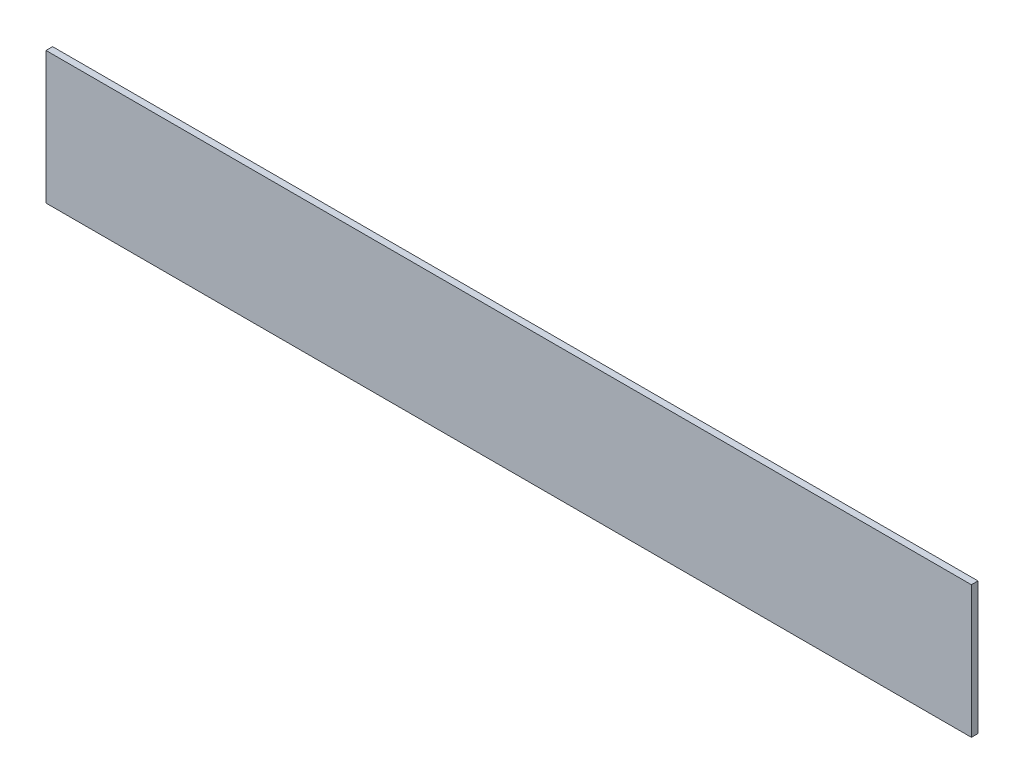
SolidWorks part; units mm, degrees
ref_plane "Front Plane" through (0, 0, 0) normal (0, 0, 1) x (1, 0, 0)
ref_plane "Top Plane" through (0, 0, 0) normal (0, 1, 0) x (1, 0, 0)
ref_plane "Right Plane" through (0, 0, 0) normal (1, 0, 0) x (0, 0, -1)
other "Configuration Table"
sketch "Sketch1" plane through (0, 0, 0) normal (0, 0, 1) x (1, 0, 0)
  line L1 (210, 360) -> (490, 360)
  line L2 (210, 360) -> (210, 400)
  line L3 (210, 400) -> (490, 400)
  line L4 (490, 360) -> (490, 400)
extrude "OVEN_kesme_bicak_1_2x28_t1.2_1" add sketch "Sketch1" against normal blind 2 from offset 299 separate body
